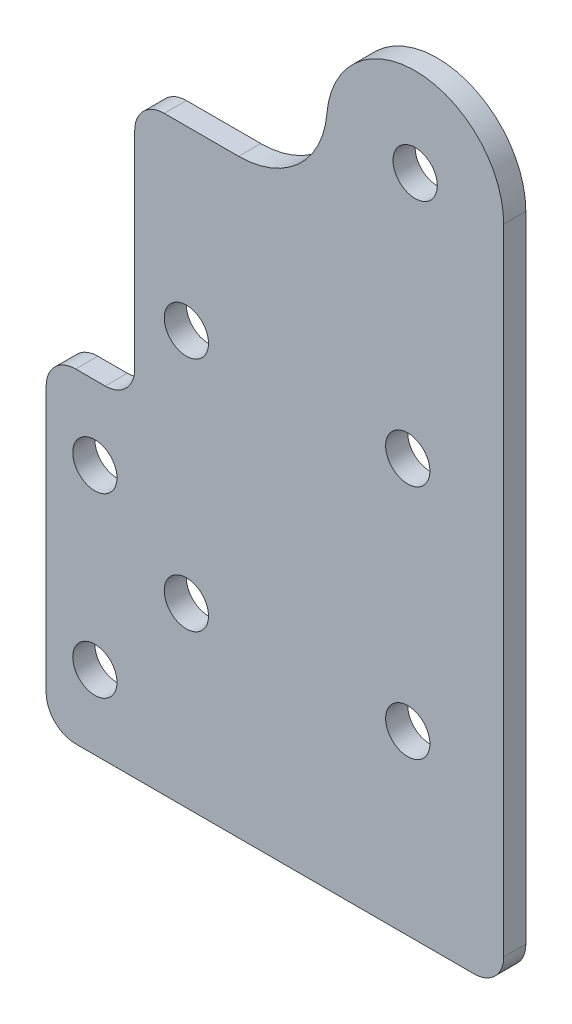
SolidWorks part; units mm, degrees
material "3.3535 (EN-AW 5754)"
ref_plane "Front" through (0, 0, 0) normal (0, 0, 1) x (1, 0, 0)
ref_plane "Top" through (0, 0, 0) normal (0, 1, 0) x (1, 0, 0)
ref_plane "Right" through (0, 0, 0) normal (1, 0, 0) x (0, 0, -1)
sketch "Esquisse1" plane through (0, 0, 0) normal (0, 0, 1) x (1, 0, 0)
  line L1 (-14, -20) -> (14, -20)
  line L2 (-14, -20) -> (-14, 20)
  line L3 (-14, 20) -> (14, 20)
  line L4 (14, -20) -> (14, 20)
  line L5 (0, 20) -> (0, -20) construction
  line L6 (-14, 0) -> (14, 0) construction
  circle A0 centre (-7.5, 8) radius 1.5
  circle A1 centre (7.5, 8) radius 1.5
  circle A2 centre (7.5, -8) radius 1.5
  circle A3 centre (-7.5, -8) radius 1.5
  point P0 (0, 0)
  dimension "D3" = 15
  dimension "D4" = 16
  dimension "D5" = 3
  dimension "D1" = 40
  dimension "D2" = 28
extrude "Boss.-Extru.1" add sketch "Esquisse1" along normal blind 1.5
sketch "Esquisse3" plane through (0, 0, 1.5) normal (0, 0, 1) x (1, 0, 0)
  line L0 (8, 20) -> (8, 25) construction
  line L1 (14, 20) -> (-14, 20) construction
  line L2 (2, 20) -> (2, 25)
  line L3 (14, 20) -> (14, 25)
  line L4 (14, -20) -> (14, 20) construction
  line L5 (-14, -20) -> (14, -20) construction
  line L6 (-14, 2) -> (-17, 2)
  line L7 (-14, 2) -> (-14, -20)
  line L8 (-14, -20) -> (-17, -20)
  line L9 (-17, 2) -> (-17, -20)
  line L10 (-14, 20) -> (-14, -20) construction
  arc A0 (2, 20) -> (14, 20) centre (8, 20) ccw
  arc A1 (14, 25) -> (2, 25) centre (8, 25) ccw
  circle A2 centre (8, 25) radius 1.5
  point P4 (8, 22.5)
  point P24 (-17, -9)
  dimension "D1" = 3
  dimension "D3" = 5
  dimension "D2" = 12
  dimension "D4" = 17
  dimension "D5" = 9
extrude "Boss.-Extru.2" add sketch "Esquisse3" against normal up to surface (1.5 mm away) up to face at (9, -8, 0)
fillet "Congé1" radius 6 1 edges at (2, 20, 0.75)
sketch "Esquisse4" plane through (0, 0, 1.5) normal (0, 0, 1) x (1, 0, 0)
  line L1 (-17, 2) -> (-17, -20) construction
  line L2 (-17, -20) -> (14, -20) construction
  line L3 (-13.7, -3) -> (-13.7, -15) construction
  line L4 (-3.9583, 20) -> (-14, 20) construction
  line L5 (-17, 2) -> (-11, 2)
  line L6 (-17, 2) -> (-17, 20)
  line L7 (-17, 20) -> (-11, 20)
  line L8 (-11, 2) -> (-11, 20)
  circle A0 centre (-13.7, -3) radius 1.5
  circle A1 centre (-13.7, -15) radius 1.5
  point P2 (-13.7, -9)
  dimension "D1" = 12
  dimension "D2" = 3.3
  dimension "D3" = 3
  dimension "D4" = 5
  dimension "D5" = 9
  dimension "D6" = 11
extrude "Enlèv. mat.-Extru.1" cut sketch "Esquisse4" against normal through all
fillet "Congé2" radius 2 5 edges at (-17, -20, 0.75) (14, -20, 0.75) (-17, 2, 0.75) (-11, 20, 0.75) (-11, 2, 0.75)
